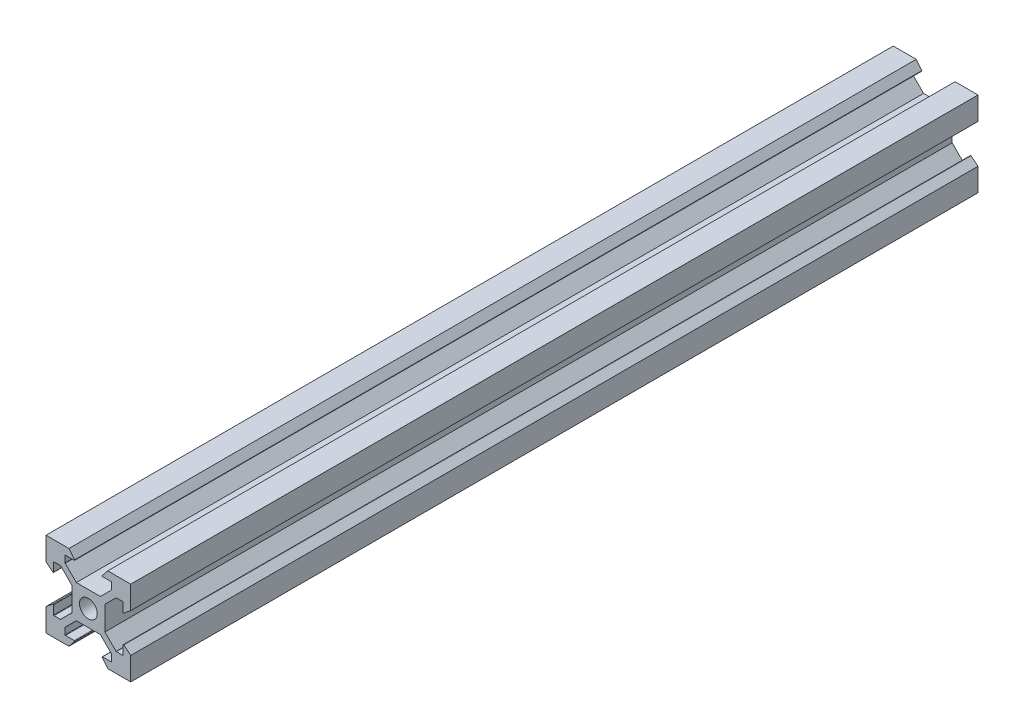
SolidWorks part; units mm, degrees
ref_plane "Front Plane" through (0, 0, 0) normal (0, 0, 1) x (1, 0, 0)
ref_plane "Top Plane" through (0, 0, 0) normal (0, 1, 0) x (1, 0, 0)
ref_plane "Right Plane" through (0, 0, 0) normal (1, 0, 0) x (0, 0, -1)
sketch "Sketch1" plane through (0, 0, 0) normal (0, 0, 1) x (1, 0, 0)
  line L0 (-2.8393, 3.9) -> (-5.4707, 6.5314)
  line L1 (-10, 10) -> (-4.58, 10)
  line L2 (-10, 10) -> (-10, 4.58)
  line L3 (-10, -10) -> (-4.58, -10)
  line L4 (10, 10) -> (10, 4.58)
  line L5 (-10, 10) -> (-3.9, 3.9) construction
  line L6 (-10, -10) -> (-4.061, -4.061) construction
  line L7 (-2.8393, 3.9) -> (2.8393, 3.9)
  line L8 (-3.9, 2.8393) -> (-3.9, -2.8393)
  line L9 (-2.8393, -3.9) -> (2.8393, -3.9)
  line L10 (3.9, 2.8393) -> (3.9, -2.8393)
  line L11 (-1.4849, 1.4849) -> (3.9, -3.9) construction
  line L12 (-3.9, -3.9) -> (1.4849, 1.4849) construction
  line L13 (-5.5, 6.6021) -> (-5.5, 8.1)
  line L14 (-5.4, 8.2) -> (-3.3344, 8.2)
  line L15 (-3.2566, 8.3629) -> (-4.58, 10)
  line L16 (0, 0) -> (0, 5.2663) construction
  line L17 (-3.9, 2.8393) -> (-6.5314, 5.4707)
  line L18 (-6.6021, 5.5) -> (-8.1, 5.5)
  line L19 (-8.2, 5.4) -> (-8.2, 3.3344)
  line L20 (-8.3629, 3.2566) -> (-10, 4.58)
  line L21 (8.3629, 3.2566) -> (10, 4.58)
  line L22 (8.2, 5.4) -> (8.2, 3.3344)
  line L23 (6.6021, 5.5) -> (8.1, 5.5)
  line L24 (3.9, 2.8393) -> (6.5314, 5.4707)
  line L25 (3.2566, 8.3629) -> (4.58, 10)
  line L26 (5.4, 8.2) -> (3.3344, 8.2)
  line L27 (2.8393, 3.9) -> (5.4707, 6.5314)
  line L28 (5.5, 6.6021) -> (5.5, 8.1)
  line L29 (55, 0) -> (-55, 0) construction
  line L30 (-8.3629, -3.2566) -> (-10, -4.58)
  line L31 (-8.2, -5.4) -> (-8.2, -3.3344)
  line L32 (-6.6021, -5.5) -> (-8.1, -5.5)
  line L33 (-3.9, -2.8393) -> (-6.5314, -5.4707)
  line L34 (-2.8393, -3.9) -> (-5.4707, -6.5314)
  line L35 (-5.5, -6.6021) -> (-5.5, -8.1)
  line L36 (-5.4, -8.2) -> (-3.3344, -8.2)
  line L37 (-3.2566, -8.3629) -> (-4.58, -10)
  line L38 (8.3629, -3.2566) -> (10, -4.58)
  line L39 (8.2, -5.4) -> (8.2, -3.3344)
  line L40 (6.6021, -5.5) -> (8.1, -5.5)
  line L41 (3.9, -2.8393) -> (6.5314, -5.4707)
  line L42 (2.8393, -3.9) -> (5.4707, -6.5314)
  line L43 (5.5, -6.6021) -> (5.5, -8.1)
  line L44 (5.4, -8.2) -> (3.3344, -8.2)
  line L45 (3.2566, -8.3629) -> (4.58, -10)
  line L46 (3.9, 3.9) -> (10, 10) construction
  line L47 (3.2459, -3.2459) -> (10, -10) construction
  line L48 (-10, -4.58) -> (-10, -10)
  line L49 (4.58, -10) -> (10, -10)
  line L50 (10, -4.58) -> (10, -10)
  line L51 (4.58, 10) -> (10, 10)
  circle A0 centre (0, 0) radius 2.1
  arc A1 (-5.4707, 6.5314) -> (-5.5, 6.6021) centre (-5.4, 6.6021) cw
  arc A2 (-5.5, 8.1) -> (-5.4, 8.2) centre (-5.4, 8.1) cw
  arc A3 (-3.3344, 8.2) -> (-3.2566, 8.3629) centre (-3.3344, 8.3) ccw
  arc A4 (-6.5314, 5.4707) -> (-6.6021, 5.5) centre (-6.6021, 5.4) ccw
  arc A5 (-8.1, 5.5) -> (-8.2, 5.4) centre (-8.1, 5.4) ccw
  arc A6 (-8.2, 3.3344) -> (-8.3629, 3.2566) centre (-8.3, 3.3344) cw
  arc A7 (8.2, 3.3344) -> (8.3629, 3.2566) centre (8.3, 3.3344) ccw
  arc A8 (8.1, 5.5) -> (8.2, 5.4) centre (8.1, 5.4) cw
  arc A9 (6.5314, 5.4707) -> (6.6021, 5.5) centre (6.6021, 5.4) cw
  arc A10 (3.3344, 8.2) -> (3.2566, 8.3629) centre (3.3344, 8.3) cw
  arc A11 (5.5, 8.1) -> (5.4, 8.2) centre (5.4, 8.1) ccw
  arc A12 (5.4707, 6.5314) -> (5.5, 6.6021) centre (5.4, 6.6021) ccw
  arc A13 (-8.2, -3.3344) -> (-8.3629, -3.2566) centre (-8.3, -3.3344) ccw
  arc A14 (-8.1, -5.5) -> (-8.2, -5.4) centre (-8.1, -5.4) cw
  arc A15 (-6.5314, -5.4707) -> (-6.6021, -5.5) centre (-6.6021, -5.4) cw
  arc A16 (-5.4707, -6.5314) -> (-5.5, -6.6021) centre (-5.4, -6.6021) ccw
  arc A17 (-5.5, -8.1) -> (-5.4, -8.2) centre (-5.4, -8.1) ccw
  arc A18 (-3.3344, -8.2) -> (-3.2566, -8.3629) centre (-3.3344, -8.3) cw
  arc A19 (8.2, -3.3344) -> (8.3629, -3.2566) centre (8.3, -3.3344) cw
  arc A20 (8.1, -5.5) -> (8.2, -5.4) centre (8.1, -5.4) ccw
  arc A21 (6.5314, -5.4707) -> (6.6021, -5.5) centre (6.6021, -5.4) ccw
  arc A22 (5.4707, -6.5314) -> (5.5, -6.6021) centre (5.4, -6.6021) cw
  arc A23 (5.5, -8.1) -> (5.4, -8.2) centre (5.4, -8.1) cw
  arc A24 (3.3344, -8.2) -> (3.2566, -8.3629) centre (3.3344, -8.3) ccw
  point P0 (0, 0)
  point P6 (0, 0)
  point P25 (-3.125, 8.2)
  dimension "D5" = 4.2
  dimension "D11" = 0.1
  dimension "D1" = 20
  dimension "D3" = 7.8
  dimension "D4" = 7.8
  dimension "D6" = 0.75
  dimension "D7" = 4.3
  dimension "D8" = 4.58
  dimension "D9" = 3.125
  dimension "D10" = 5.5
extrude "Boss-Extrude1" add sketch "Sketch1" along normal blind 200
